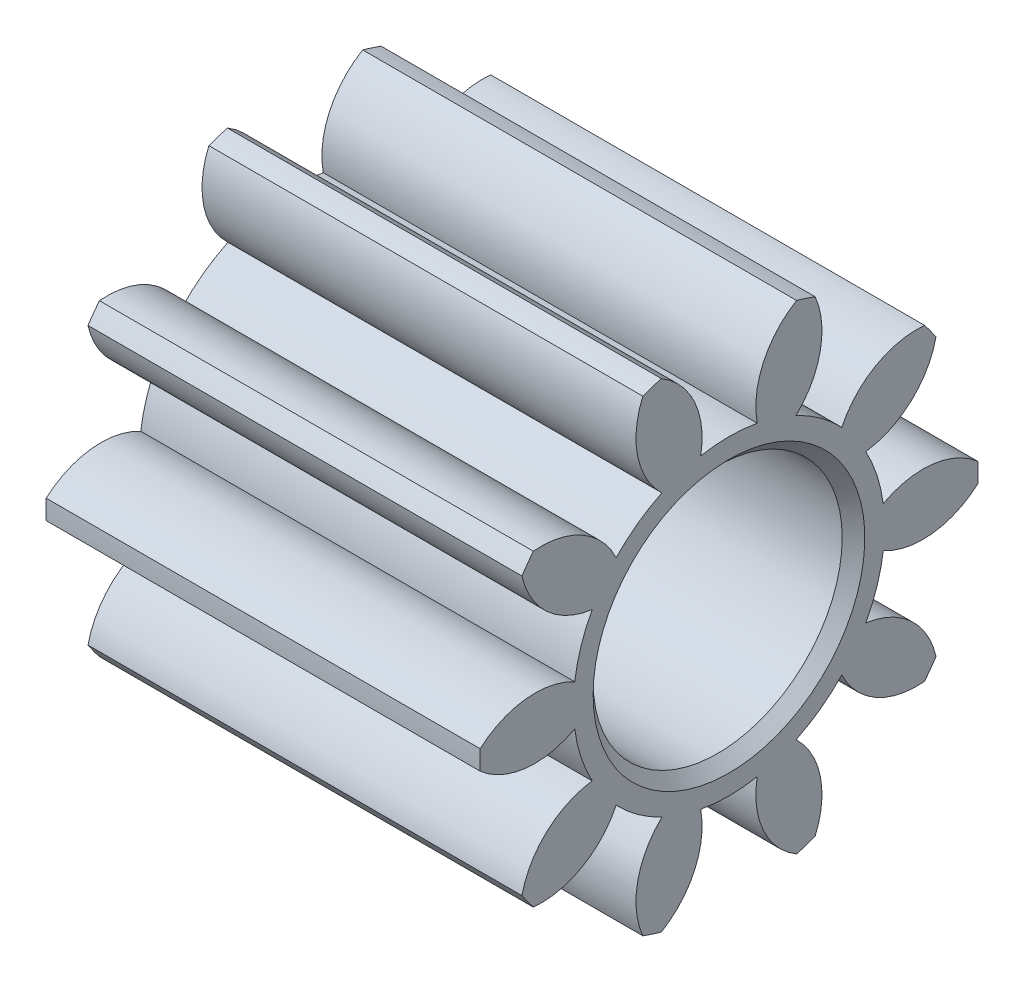
SolidWorks part; units mm, degrees
ref_plane "Plane1" through (0, 0, 0) normal (0, 0, 1) x (1, 0, 0)
ref_plane "Plane2" through (0, 0, 0) normal (0, 1, 0) x (1, 0, 0)
ref_plane "Plane3" through (0, 0, 0) normal (1, 0, 0) x (0, 0, -1)
other "Configuration Table"
sketch "HoldingSke" plane through (0, 0, 0) normal (0, 1, 0) x (1, 0, 0)
  line L0 (0, 0) -> (0.8953, -0.1579)
  line L1 (-15, 0) -> (100, 0) construction
  line L2 (0, 0) -> (-2.1039, 2.3779)
  line L3 (0, 0) -> (-11.863, 4.5341)
  line L4 (0, 0) -> (8.5048, 1.4996)
  line L5 (0, 0) -> (-46.8476, -17.4728)
  line L6 (0, 0) -> (-9.5331, -6.432)
  line L7 (-2.1039, 2.3779) -> (8.6587, 51.2062)
  line L8 (-76.2, 54.61) -> (-75.7, 54.61)
  line L9 (-67.7845, 28.3722) -> (-49.3413, 33.142)
  line L10 (-76.2, 71.12) -> (104.1128, 71.12)
  line L11 (0, 0) -> (-11.5, 0)
  line L12 (-76.2, 101.6) -> (-76.158, 101.6)
  line L13 (24.9733, 27.94) -> (52.9518, 28.4284)
  line L14 (24.9733, 27.94) -> (24.9743, 27.94)
  line L15 (24.9733, 27.94) -> (100.4006, 29.5858)
  line L16 (-63.627, -1.1) -> (-12.827, -1.1)
  circle A0 centre (0, 0) radius 1.5
  circle A1 centre (0, 0) radius 4.124
  circle A2 centre (0, 0) radius 37.5
  circle A3 centre (0, 0) radius 1.5
  dimension "MHD" = 8.248
  dimension "Hub_dia" = 75
  dimension "Bore" = 3
  dimension "MBD" = 3
  dimension "Num_teeth" = 10
  dimension "Pitch" = 0.9091
  dimension "Overall_len" = 50
  dimension "Show_teeth" = 10
  dimension "Thickness" = 11.5
  dimension "OAL" = 50.0004
  dimension "T_dim" = 0.5
  dimension "Ap" = 14.5
  dimension "H" = 19.05
  dimension "Pitch_radius" = 180.3128
  dimension "Width" = 11.5
  dimension "Backlash" = 0.042
  dimension "Addendum_fac" = 1
  dimension "Dedendum_fac" = 1.25
  dimension "Clearance_fac" = 0.25
  dimension "Dedendum_add" = 0.001
  dimension "Module" = 1.1
sketch "BasProSke" plane through (0, 0, 0) normal (0, 1, 0) x (1, 0, 0)
  line L0 (-10, 0) -> (60, 0) construction
  line L1 (0, 0) -> (0, 6.6)
  line L2 (0, 0) -> (11.5, 0)
  line L3 (11.5, 0) -> (11.5, 6.6)
  line L4 (11.5, 6.6) -> (0, 6.6)
  dimension "Thickness" = 11.5
  dimension "Diameter" = 13.2
revolve "Base-Revolve" add sketch "BasProSke" angle 360 about L0
sketch "TooCutSke" plane through (0, 0, 0) normal (1, 0, 0) x (0, 0, -1)
  line L1 (0, 0) -> (0, 107) construction
  line L2 (0, 0) -> (-0.9337, 5.4202) construction
  line L3 (0, 0) -> (-3.3642, 10.354) construction
  line L4 (-0.9337, 5.4202) -> (-1.6821, 5.177) construction
  arc A0 (0.7493, 4.0554) -> (-0.7493, 4.0554) centre (0, 0) ccw
  arc A1 (1.8233, 6.3696) -> (-1.8233, 6.3696) centre (0, 0) ccw
  circle A2 centre (0, 0) radius 5.5 construction
  circle A3 centre (0, 0) radius 5.3248 construction
  arc A4 (-0.7493, 4.0554) -> (-1.8233, 6.3696) centre (-2.9121, 4.4579) ccw
  arc A5 (1.8233, 6.3696) -> (0.7493, 4.0554) centre (2.9121, 4.4579) ccw
  dimension "Root_dia" = 8.248
  dimension "Overcut_dia" = 13.2508
  dimension "Pitch_dia" = 11
  dimension "Base_dia" = 10.6496
  dimension "Flank_rad" = 2.2
  dimension "Half_ang" = 18
  dimension "Half_CT" = 0.7869
extrude "ToothCut" cut sketch "TooCutSke" along normal through all
fillet "Breaks" [suppressed] radius 0.022
fillet "RootFillets" [suppressed] radius 0.276
pattern_circular "TeethCuts" count 10 every 36 about axis through (-10, 0, 0) along (1, 0, 0) of "ToothCut", "RootFillets", "Breaks"
sketch "HubNeaOneSke" plane through (0, 0, 0) normal (-1, 0, 0) x (0, 0, 1)
  circle A0 centre (0, 0) radius 4.124
  dimension "Diameter" = 8.248
extrude "HubNearOne" [suppressed] add sketch "HubNeaOneSke" along normal blind 38.5004
sketch "HubNeaBotSke" plane through (0, 0, 0) normal (-1, 0, 0) x (0, 0, 1)
  circle A0 centre (0, 0) radius 4.124
  dimension "Diameter" = 8.248
extrude "HubNearBoth" [suppressed] add sketch "HubNeaBotSke" along normal blind 19.2502
ref_plane "FarPln" through (11.5, 0, 0) normal (1, 0, 0) x (0, 0, -1)
sketch "HubFarSke" plane through (11.5, 0, 0) normal (1, 0, 0) x (0, 0, -1)
  circle A0 centre (0, 0) radius 4.124
  dimension "Diameter" = 8.248
extrude "HubFar" [suppressed] add sketch "HubFarSke" along normal blind 19.2502
sketch "BorSke" plane through (0, 0, 0) normal (1, 0, 0) x (0, 0, -1)
  circle A0 centre (0, 0) radius 1.5
  dimension "Diameter" = 3
extrude "Bore" cut sketch "BorSke" along normal mid plane 100.0007
sketch "KeySke" plane through (0, 0, 0) normal (1, 0, 0) x (0, 0, -1)
  line L0 (-0.6, 0) -> (-0.6, 2)
  line L1 (-0.6, 2) -> (0.6, 2)
  line L2 (0.6, 2) -> (0.6, 0)
  line L3 (0, 0) -> (0, 34) construction
  line L4 (-0.6, 0) -> (0.6, 0)
  dimension "Offset" = 2
  dimension "Width" = 1.2
extrude "Keyway" [suppressed] cut sketch "KeySke" along normal mid plane 100.0007
pattern_circular "Keyway2" [suppressed] count 2 every 90 about axis through (-10, 0, 0) along (1, 0, 0)
sketch "Sketch2" plane through (11.5, 0, 0) normal (1, 0, 0) x (0, 0, -1)
  circle A3 centre (0, 0) radius 3.3
  dimension "D1" = 6.6
extrude "Cut-Extrude1" cut sketch "Sketch2" against normal blind 5.5
sketch "Sketch3" plane through (0, 0, 0) normal (-1, 0, 0) x (0, 0, 1)
  circle A0 centre (0, 0) radius 3.3
  dimension "D1" = 6.6
extrude "Cut-Extrude2" cut sketch "Sketch3" against normal blind 3.3
sketch "Sketch4" plane through (3.3, 0, 0) normal (-1, 0, 0) x (0, 0, 1)
  circle A0 centre (0, 0) radius 1.65
  dimension "D1" = 3.3
extrude "Cut-Extrude3" cut sketch "Sketch4" against normal through all
chamfer "Chamfer1" distance 0.3 angle 45 2 edges at (11.5, 0, -3.3) (0, 0, 3.3)
equation "' \"Module@HoldingSke\" = 6.35"
equation "' \"Num_teeth@HoldingSke\" = 12"
equation "' \"Ap@HoldingSke\" =  20"
equation "' \"Ap@HoldingSke\" = 20"
equation "' \"Width@HoldingSke\" = 0.5 * 25.4"
equation "' \"Hub_dia@HoldingSke\"= 1 * 25.4"
equation "' \"Hub_dia@HoldingSke\" = 1 * 25.4"
equation "' \"Overall_len@HoldingSke\" = 1.0 * 25.4"
equation "' \"Bore@HoldingSke\" = 0.75 * 25.4"
equation "' \"T_dim@HoldingSke\" = 0.1 * 25.4"
equation "' \"Width@KeySke\" = 0.25 * 25.4"
equation "' \"Show_teeth@HoldingSke\" = 13"
equation "' \"Backlash@HoldingSke\" = 0.009 * 25.4"
equation "' \"Addendum_fac@HoldingSke\" = 1.0"
equation "' \"Dedendum_fac@HoldingSke\" = 1.25"
equation "' \"Dedendum_add@HoldingSke\" = 0.00005 * 25.4"
equation "' \"Clearance_fac@HoldingSke\" = 0.25"
equation "\"Pitch@HoldingSke\" = 1 / \"Module@HoldingSke\""
equation "\"Overcut_dia@TooCutSke\" = (\"Num_teeth@HoldingSke\" + 2 * \"Addendum_fac@HoldingSke\") / \"Pitch@HoldingSke\" + 0.002 * 25.4"
equation "\"Pitch_dia@TooCutSke\" = \"Num_teeth@HoldingSke\" / \"Pitch@HoldingSke\""
equation "\"Base_dia@TooCutSke\" = \"Num_teeth@HoldingSke\" / \"Pitch@HoldingSke\" * cos((\"Ap@HoldingSke\"  * 3.14159265 / 180))"
equation "\"Root_dia@TooCutSke\" = (\"Num_teeth@HoldingSke\" + 2) / \"Pitch@HoldingSke\" - 2 * (\"Addendum_fac@HoldingSke\" + \"Dedendum_fac@HoldingSke\") / \"Pitch@HoldingSke\" - \"Dedendum_add@HoldingSke\" * 2"
equation "\"Half_ang@TooCutSke\" = 180 / \"Num_teeth@HoldingSke\""
equation "\"Half_CT@TooCutSke\" = \"Num_teeth@HoldingSke\" / \"Pitch@HoldingSke\" * sin((3.14159265 / 2 / \"Num_teeth@HoldingSke\")) / 2 - 7 * \"Backlash@HoldingSke\" / 4"
equation "\"Flank_rad@TooCutSke\" = \"Num_teeth@HoldingSke\" / \"Pitch@HoldingSke\" / 5"
equation "\"Radius@RootFillets\" = \"Clearance_fac@HoldingSke\" / \"Pitch@HoldingSke\" + \"Dedendum_add@HoldingSke\""
equation "\"Break_rad@Breaks\" = 0.02 / \"Pitch@HoldingSke\""
equation "\"Thickness@HoldingSke\" = \"Width@HoldingSke\""
equation "\"OAL@HoldingSke\" = \"Thickness@HoldingSke\""
equation "\"MHD@HoldingSke\" = (\"Num_teeth@HoldingSke\" + 2) / \"Pitch@HoldingSke\" - 2 * (\"Addendum_fac@HoldingSke\" + \"Dedendum_fac@HoldingSke\")  / \"Pitch@HoldingSke\" - \"Dedendum_add@HoldingSke\" * 2"
equation "\"MBD@HoldingSke\" = (\"Num_teeth@HoldingSke\" + 2) / \"Pitch@HoldingSke\" - 2 * (\"Addendum_fac@HoldingSke\" + \"Dedendum_fac@HoldingSke\")  / \"Pitch@HoldingSke\" - \"Dedendum_add@HoldingSke\" * 2 - 0.002 * 25.4"
equation "\"MHD@HoldingSke\" = ((sgn( \"MHD@HoldingSke\" - \"Hub_dia@HoldingSke\" )-1)*( \"MHD@HoldingSke\" - \"Hub_dia@HoldingSke\" ))/-2+ \"Hub_dia@HoldingSke\""
equation "\"MBD@HoldingSke\" = ((sgn( \"MBD@HoldingSke\" - \"Bore@HoldingSke\" )-1)*( \"MBD@HoldingSke\" - \"Bore@HoldingSke\" ))/-2+ \"Bore@HoldingSke\""
equation "\"OAL@HoldingSke\" = ((sgn( \"OAL@HoldingSke\" - \"Overall_len@HoldingSke\" )+1)*( \"OAL@HoldingSke\" - \"Overall_len@HoldingSke\" ))/2 + \"Overall_len@HoldingSke\" + 0.000002 * 25.4"
equation "\"Num_teeth@TeethCuts\" = int( \"Show_teeth@HoldingSke\" ) + 1"
equation "\"Num_teeth@TeethCuts\" = ((sgn( \"Num_teeth@TeethCuts\" - \"Num_teeth@HoldingSke\" )-1)*( \"Num_teeth@TeethCuts\" - \"Num_teeth@HoldingSke\" ))/-2+ \"Num_teeth@HoldingSke\""
equation "\"Num_teeth@TeethCuts\" = ((sgn( \"Num_teeth@TeethCuts\" - 2.0)+1)*( \"Num_teeth@TeethCuts\" - 2.0))/2 +2.0"
equation "\"Angle@TeethCuts\" = 360.0 / \"Num_teeth@HoldingSke\""
equation "\"Diameter@BasProSke\" = (\"Num_teeth@HoldingSke\" + 2 * \"Addendum_fac@HoldingSke\") / \"Pitch@HoldingSke\""
equation "\"Thickness@BasProSke\"  = \"Thickness@HoldingSke\""
equation "' \"Fillet_rad@BasProSke\" =  \"Thickness@HoldingSke\" * 0.05"
equation "' \"Fillet_rad@BasProSke\" = \"Thickness@HoldingSke\" * 0.05"
equation "\"MHD@HoldingSke\" = ((sgn( \"MHD@HoldingSke\" - \"Root_dia@TooCutSke\" )-1)*( \"MHD@HoldingSke\" - \"Root_dia@TooCutSke\" ))/-2+ \"Root_dia@TooCutSke\""
equation "\"Diameter@HubNeaOneSke\" = \"MHD@HoldingSke\""
equation "\"Length@HubNearOne\" = \"OAL@HoldingSke\" - \"Thickness@BasProSke\""
equation "\"Diameter@HubNeaBotSke\" = \"MHD@HoldingSke\""
equation "\"Length@HubNearBoth\" = ( \"OAL@HoldingSke\" - \"Thickness@BasProSke\" ) / 2.0"
equation "\"Thickness@FarPln\" = \"Thickness@BasProSke\""
equation "\"Diameter@HubFarSke\" = \"MHD@HoldingSke\""
equation "\"Length@HubFar\" = ( \"OAL@HoldingSke\" - \"Thickness@BasProSke\" ) / 2.0"
equation "\"Diameter@BorSke\" = \"MBD@HoldingSke\""
equation "\"D1@Bore\" = \"OAL@HoldingSke\" * 2.0"
equation "\"D1@Keyway\" = \"OAL@HoldingSke\" * 2.0"
equation "\"Offset@KeySke\" = \"T_dim@HoldingSke\" + \"MBD@HoldingSke\" / 2.0"
